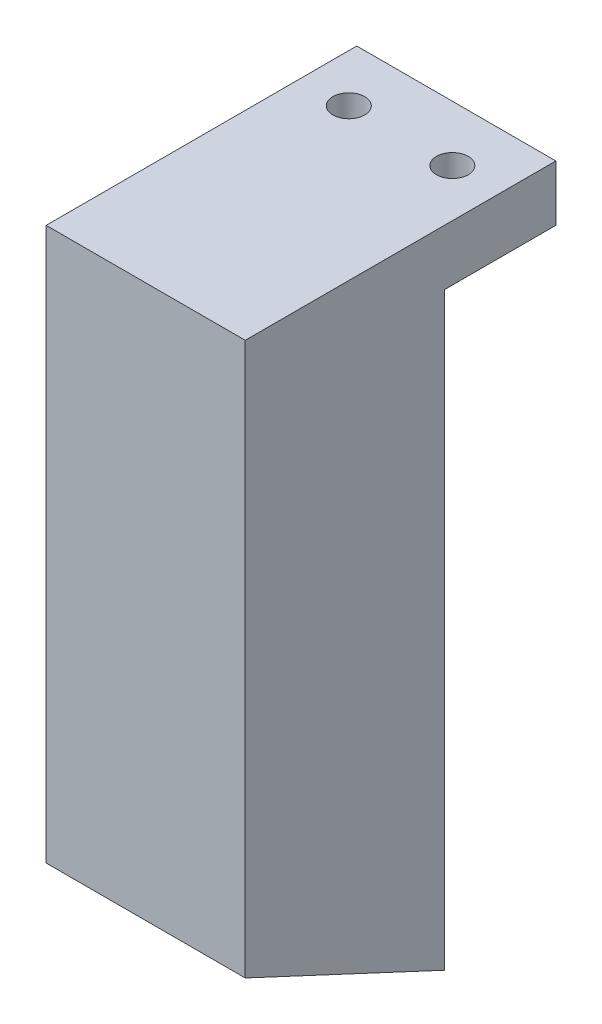
SolidWorks part; units mm, degrees
material "ABS"
ref_plane "Front Plane" through (0, 0, 0) normal (0, 0, 1) x (1, 0, 0)
ref_plane "Top Plane" through (0, 0, 0) normal (0, 1, 0) x (1, 0, 0)
ref_plane "Right Plane" through (0, 0, 0) normal (1, 0, 0) x (0, 0, -1)
sketch "Sketch1" plane through (0, 0, 0) normal (0, 1, 0) x (1, 0, 0)
  line L1 (-76.9048, 16.0714) -> (-51.9048, 16.0714)
  line L2 (-76.9048, 16.0714) -> (-76.9048, -8.9286)
  line L3 (-76.9048, -8.9286) -> (-51.9048, -8.9286)
  line L4 (-51.9048, 16.0714) -> (-51.9048, -8.9286)
  dimension "D1" = 25
  dimension "D2" = 25
extrude "Boss-Extrude1" add sketch "Sketch1" along normal blind 81
sketch "Sketch2" plane through (-51.9048, 0, 0) normal (1, 0, 0) x (0, 0, -1)
  line L3 (-8.9286, 0) -> (16.0714, 0) construction
  line L5 (16.0714, 0) -> (-8.9286, 0)
  line L6 (16.0714, 81) -> (16.0714, 0) construction
  line L7 (-8.9286, 81) -> (-8.9286, 0) construction
  line L8 (-8.9286, 0) -> (-8.9286, 11.6577)
  line L9 (-8.9286, 11.6577) -> (16.0714, 0)
  dimension "D1" = 25
  dimension "D2" = 0
extrude "Cut-Extrude1" cut sketch "Sketch2" against normal blind 40
sketch "Sketch3" plane through (0, 6.1557, -2.8705) normal (0, -0.9063, 0.4226) x (1, 0, 0)
  line L0 (-76.9048, 13.0188) -> (-51.9048, 13.0188) construction
  line L1 (-51.9048, -14.5657) -> (-51.9048, 13.0188) construction
  circle A0 centre (-64.4048, -0.7712) radius 1.5
  point P4 (-64.4048, 13.0188)
  dimension "D1" = 13.79
  dimension "D2" = 12.5
  dimension "D3" = 3
extrude "Cut-Extrude2" cut sketch "Sketch3" against normal blind 36
sketch "Sketch4" plane through (0, 0, -16.0714) normal (0, 0, -1) x (-1, 0, 0)
  line L0 (51.9048, 81) -> (51.9048, 0) construction
  line L1 (76.9048, 81) -> (51.9048, 81)
  line L2 (76.9048, 81) -> (76.9048, 74)
  line L3 (76.9048, 74) -> (51.9048, 74)
  line L4 (51.9048, 81) -> (51.9048, 74)
  dimension "D1" = 7
extrude "Boss-Extrude2" add sketch "Sketch4" along normal blind 14
sketch "Sketch5" plane through (0, 74, 0) normal (0, -1, 0) x (-1, 0, 0)
  line L0 (51.9048, 30.0714) -> (76.9048, 30.0714) construction
  line L1 (51.9048, 30.0714) -> (51.9048, 16.0714) construction
  line L2 (76.9048, 30.0714) -> (76.9048, 16.0714) construction
  circle A0 centre (70.9048, 23.0714) radius 2
  circle A1 centre (57.9048, 23.0714) radius 2
  dimension "D1" = 4
  dimension "D2" = 4
  dimension "D3" = 7
  dimension "D4" = 6
  dimension "D5" = 6
  dimension "D6" = 7
extrude "Cut-Extrude3" cut sketch "Sketch5" against normal blind 14
